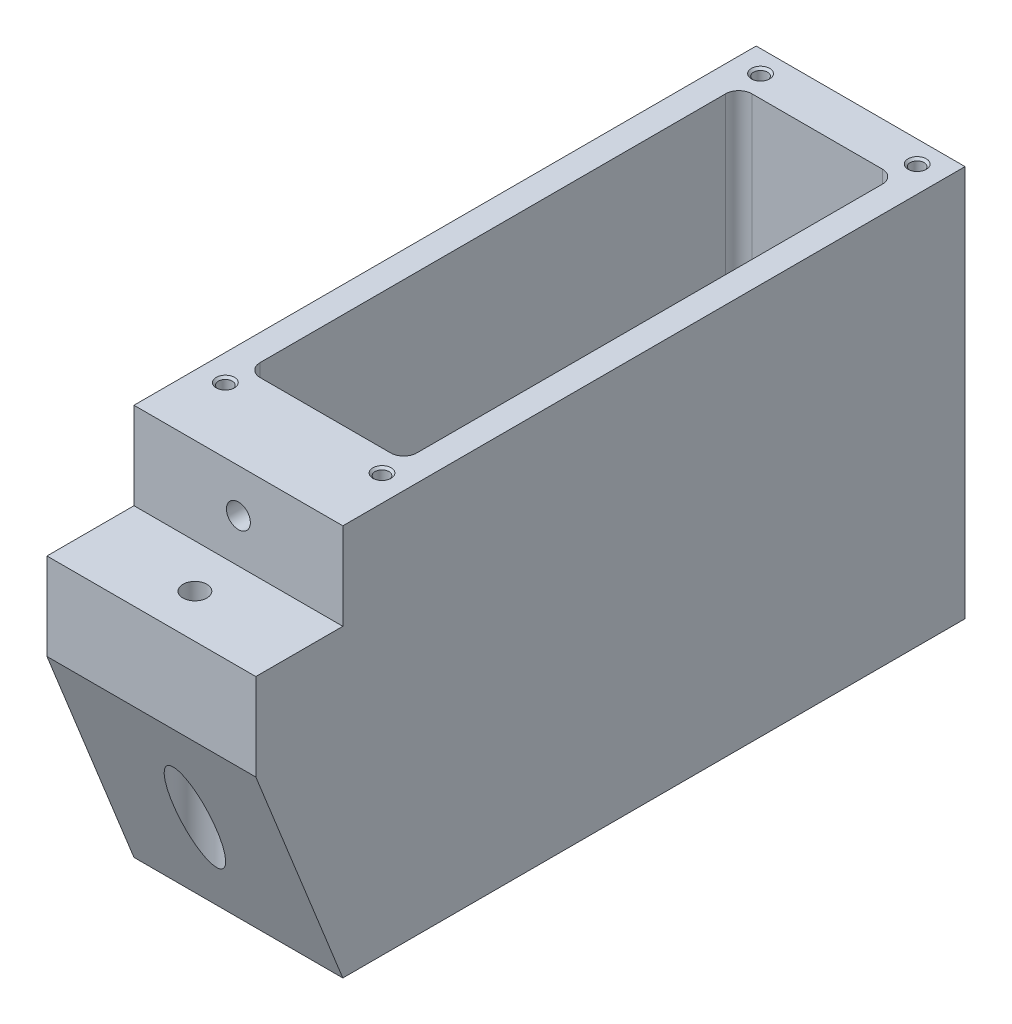
SolidWorks part; units mm, degrees
material "PLA"
ref_plane "Front Plane" through (0, 0, 0) normal (0, 0, 1) x (1, 0, 0)
ref_plane "Top Plane" through (0, 0, 0) normal (0, 1, 0) x (1, 0, 0)
ref_plane "Right Plane" through (0, 0, 0) normal (1, 0, 0) x (0, 0, -1)
sketch "Sketch1" plane through (0, 0, 0) normal (1, 0, 0) x (0, 0, -1)
  line L0 (0, 0) -> (0, -20)
  line L1 (0, -20) -> (-20, -20)
  line L2 (-20, -20) -> (-20, -40)
  line L3 (0, 0) -> (20, 0)
  line L4 (-20, -40) -> (0, -90)
  line L5 (0, -90) -> (143, -90)
  line L6 (143, -90) -> (143, 0)
  line L7 (133, 0) -> (133, -76.5)
  line L8 (133, -76.5) -> (20, -76.5)
  line L9 (20, -76.5) -> (20, 0)
  line L10 (133, 0) -> (143, 0)
  line L11 (20, 0) -> (133, 0) construction
  line L12 (0, -20) -> (0, -90) construction
  dimension "D1" = 20
  dimension "D2" = 20
  dimension "D3" = 76.5
  dimension "D4" = 90
  dimension "D5" = 10
  dimension "D6" = 113
extrude "Boss-Extrude1" add sketch "Sketch1" along normal blind 9
sketch "Sketch2" plane through (0, 0, 0) normal (-1, 0, 0) x (0, 0, 1)
  line L11 (0, 0) -> (-20, 0)
  line L12 (-20, 0) -> (-20, -76.5)
  line L13 (-20, -76.5) -> (-133, -76.5)
  line L14 (-133, -76.5) -> (-133, 0)
  line L15 (-133, 0) -> (-143, 0)
  line L16 (-143, 0) -> (-143, -90)
  line L17 (-143, -90) -> (0, -90)
  line L18 (0, -90) -> (20, -40)
  line L19 (20, -40) -> (20, -20)
  line L20 (20, -20) -> (0, -20)
  line L21 (0, -20) -> (0, 0)
  line L22 (0, 0) -> (-143, 0)
  line L27 (-143, 0) -> (-143, -90)
  line L28 (-143, -90) -> (0, -90)
  line L29 (0, -90) -> (20, -40)
  line L30 (20, -40) -> (20, -20)
  line L31 (20, -20) -> (0, -20)
  line L32 (0, -20) -> (0, 0)
  dimension "D1" = 0
extrude "Boss-Extrude2" add sketch "Sketch2" along normal blind 6
sketch "Sketch3" plane through (9, 0, 0) normal (1, 0, 0) x (0, 0, -1)
  line L0 (0, -90) -> (143, -90) construction
  line L1 (0, -90) -> (20, -90)
  line L2 (133, -90) -> (143, -90)
  line L11 (20, 0) -> (0, 0)
  line L12 (0, 0) -> (0, -20)
  line L13 (0, -20) -> (-20, -20)
  line L14 (-20, -20) -> (-20, -40)
  line L15 (-20, -40) -> (0, -90)
  line L16 (0, -90) -> (143, -90)
  line L17 (143, -90) -> (143, 0)
  line L18 (143, 0) -> (133, 0)
  line L19 (133, 0) -> (133, -76.5)
  line L20 (133, -76.5) -> (20, -76.5)
  line L21 (20, -76.5) -> (20, 0)
  line L22 (20, 0) -> (0, 0)
  line L23 (0, 0) -> (0, -20)
  line L24 (0, -20) -> (-20, -20)
  line L25 (-20, -20) -> (-20, -40)
  line L26 (-20, -40) -> (0, -90)
  line L28 (143, -90) -> (143, 0)
  line L29 (143, 0) -> (133, 0)
  line L30 (133, 0) -> (133, -90)
  line L32 (20, -90) -> (20, 0)
  dimension "D1" = 0
extrude "Boss-Extrude3" add sketch "Sketch3" along normal blind 9
fillet "Fillet1" radius 3 4 edges at (9, -83.25, -20) (9, -83.25, -133) (4.5, -76.5, -133) (4.5, -76.5, -20)
ref_plane "Plane1" through (18, 0, 0) normal (1, 0, 0) x (0, 0, -1)
mirror "Mirror4" about plane through (18, 0, 0) normal (1, 0, 0) of "Fillet1", "Boss-Extrude3", "Boss-Extrude2", "Boss-Extrude1"
fillet "Fillet2" radius 3 10 edges at (36, -36.75, -133) (36, -75.6213, -132.1213) (36, -76.5, -76.5) (36, -75.6213, -20.8787) (0, -36.75, -133) (0, -75.6213, -132.1213) (0, -76.5, -76.5) (0, -75.6213, -20.8787) (36, -36.75, -20) (0, -36.75, -20)
sketch "Sketch4" plane through (0, 0, 0) normal (0, 1, 0) x (1, 0, 0)
  line L3 (0, 143) -> (0, 133) construction
  line L5 (0, 20) -> (0, 10) construction
  line L6 (0, 23) -> (0, 20) construction
  line L7 (0, 20) -> (3, 20) construction
  line L9 (33, 20) -> (36, 20) construction
  line L10 (36, 20) -> (36, 23) construction
  line L12 (0, 130) -> (0, 133) construction
  line L13 (0, 133) -> (3, 133) construction
  line L15 (33, 133) -> (36, 133) construction
  line L16 (36, 133) -> (36, 130) construction
  line L18 (42, 143) -> (-6, 143) construction
  line L19 (36, 20) -> (36, 10) construction
  line L21 (36, 133) -> (36, 143) construction
  point P7 (0, 138)
  point P11 (0, 15)
  point P61 (36, 15)
  point P63 (36, 138)
hole_wizard "Ø2.5mm Dowel Hole1" positions "Sketch4" profile "Sketch5" hole size "Ø2.5" standard "ANSI Metric"
sketch "Sketch5" plane through (36, 0, -138) normal (1, 0, 0) x (0, 0, 1)
  line L0 (0, 0) -> (0, 7.4614)
  line L1 (0, 7.4614) -> (1.6, 6.5)
  line L2 (1.6, 6.5) -> (1.6, 0)
  line L5 (1.6, 0) -> (0, 0)
  line L10 (0, 7.4614) -> (-1.6, 6.5) construction
  line L11 (0, -6.35) -> (0, 107.95) construction
  dimension "Hole Dia." = 3.2
  dimension "Hole Depth" = 6.5
  dimension "Drill Angle" = 118
chamfer "Chamfer1" distance 0.5 angle 45 4 edges at (0, 0, -136.4) (0, 0, -13.4) (36, 0, -13.4) (36, 0, -136.4)
ref_plane "Plane2" through (0, -40, 0) normal (0, 1, 0) x (1, 0, 0)
sketch "Sketch6" plane through (0, -40, 0) normal (0, 1, 0) x (1, 0, 0)
  line L0 (-6, -10) -> (42, -10) construction
  line L1 (-6, -20) -> (-6, 0) construction
  line L2 (42, -20) -> (42, 0) construction
  point P6 (18, -10)
hole_wizard "CBORE for M5 SHCS1" positions "Sketch6" profile "Sketch7" counterbore size "M5" standard "ANSI Metric"
sketch "Sketch7" plane through (18, -40, 10) normal (1, 0, 0) x (0, 0, -1)
  line L0 (0, 0) -> (0, 40)
  line L1 (0, 40) -> (2.75, 40)
  line L3 (2.75, 40) -> (2.75, 5)
  line L4 (2.75, 5) -> (5, 5)
  line L5 (5, 5) -> (5, 0)
  line L7 (5, 0) -> (0, 0)
  line L11 (0, -6.35) -> (0, 107.95) construction
  dimension "Thru Hole Dia." = 5.5
  dimension "Thru Hole Depth" = 40
  dimension "C'Bore Dia." = 10
  dimension "C'Bore Depth" = 5
sketch "Sketch8" plane through (0, -40, 0) normal (0, 1, 0) x (1, 0, 0)
  circle A1 centre (18, -10) radius 5
  circle A2 centre (18, -10) radius 5
  dimension "D1" = 0
extrude "Cut-Extrude1" cut sketch "Sketch8" against normal through all
sketch "Sketch9" plane through (0, 0, -20) normal (0, 0, -1) x (-1, 0, 0)
  line L0 (6, -10) -> (-42, -10) construction
  line L1 (6, -20) -> (6, 0) construction
  line L2 (-42, -20) -> (-42, 0) construction
  point P6 (-18, -10)
hole_wizard "CBORE for M5 SHCS2" positions "Sketch9" profile "Sketch10" counterbore size "M5" standard "ANSI Metric"
sketch "Sketch10" plane through (18, -10, -20) normal (1, 0, 0) x (0, 1, 0)
  line L0 (0, 0) -> (0, 40)
  line L1 (0, 40) -> (2.75, 40)
  line L3 (2.75, 40) -> (2.75, 5)
  line L4 (2.75, 5) -> (5, 5)
  line L5 (5, 5) -> (5, 0)
  line L7 (5, 0) -> (0, 0)
  line L11 (0, -6.35) -> (0, 107.95) construction
  dimension "Thru Hole Dia." = 5.5
  dimension "Thru Hole Depth" = 40
  dimension "C'Bore Dia." = 10
  dimension "C'Bore Depth" = 5
